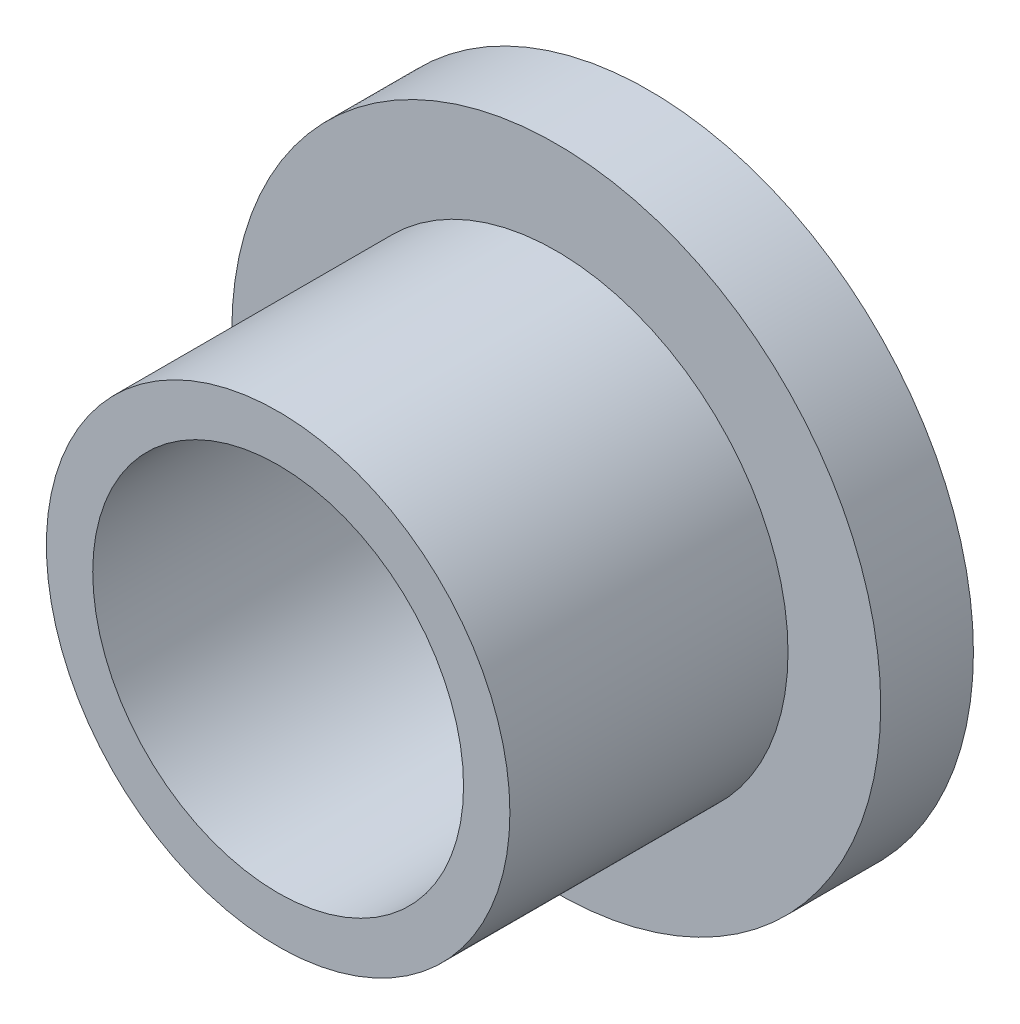
SolidWorks part; units mm, degrees
ref_plane "Front Plane" through (0, 0, 0) normal (0, 0, 1) x (1, 0, 0)
ref_plane "Top Plane" through (0, 0, 0) normal (0, 1, 0) x (1, 0, 0)
ref_plane "Right Plane" through (0, 0, 0) normal (1, 0, 0) x (0, 0, -1)
sketch "Sketch1" plane through (0, 0, 0) normal (1, 0, 0) x (0, 0, -1)
  line L0 (-43.3805, 0) -> (116.3699, 0) construction
  line L1 (0, 6.35) -> (0, 7.9375)
  line L2 (0, 7.9375) -> (9.525, 7.9375)
  line L3 (9.525, 7.9375) -> (9.525, 11.1125)
  line L4 (9.525, 11.1125) -> (12.7, 11.1125)
  line L5 (12.7, 11.1125) -> (12.7, 6.35)
  line L6 (12.7, 6.35) -> (0, 6.35)
  dimension "D1" = 12.7
  dimension "D2" = 15.875
  dimension "D3" = 22.225
  dimension "D4" = 3.175
  dimension "D5" = 12.7
revolve "Revolve1" add sketch "Sketch1" angle 360 about L0
